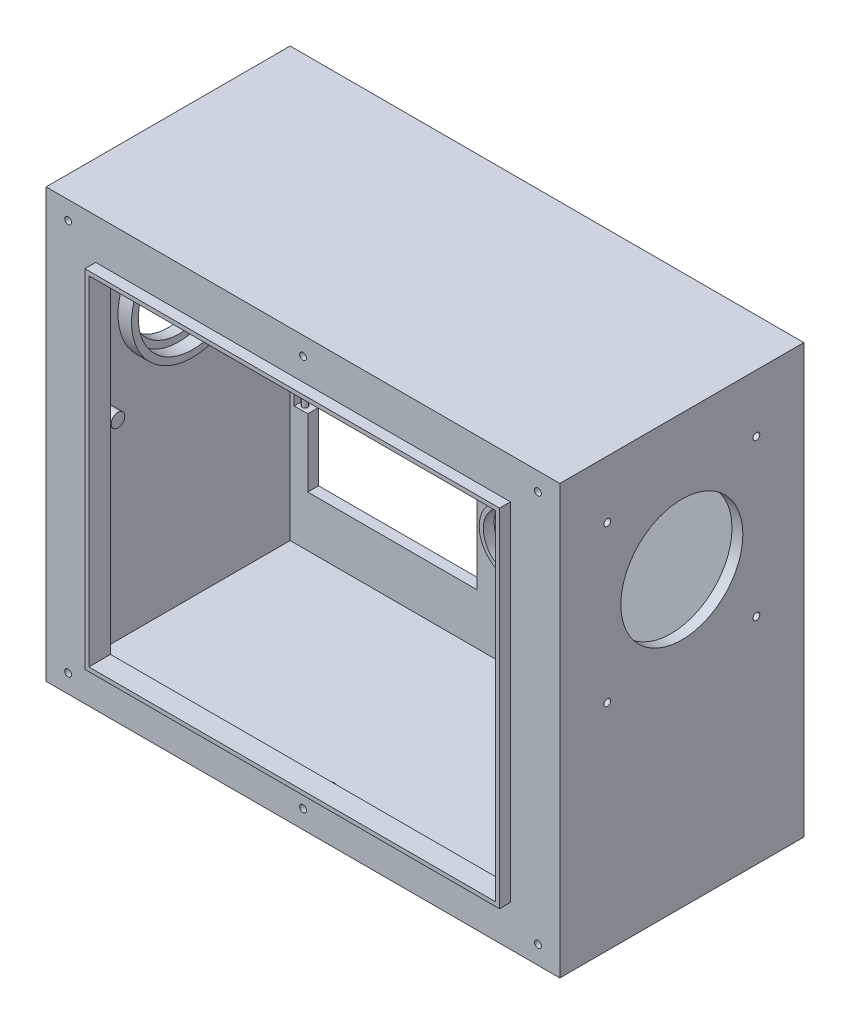
SolidWorks part; units mm, degrees
ref_plane "Alzado" through (0, 0, 0) normal (0, 0, 1) x (1, 0, 0)
ref_plane "Planta" through (0, 0, 0) normal (0, 1, 0) x (1, 0, 0)
ref_plane "Vista lateral" through (0, 0, 0) normal (1, 0, 0) x (0, 0, -1)
sketch "Croquis1" plane through (0, 0, 0) normal (0, 0, 1) x (1, 0, 0)
  line L0 (-189.5, 158) -> (189.5, 158)
  line L1 (-181.5, -150) -> (181.5, -150) construction
  line L2 (-181.5, -150) -> (-181.5, 150) construction
  line L3 (-181.5, 150) -> (181.5, 150) construction
  line L4 (181.5, -150) -> (181.5, 150) construction
  line L5 (-181.5, -150) -> (181.5, 150) construction
  line L6 (-181.5, 150) -> (181.5, -150) construction
  line L7 (189.5, -158) -> (189.5, 158)
  line L8 (-189.5, -158) -> (189.5, -158)
  line L9 (-189.5, -158) -> (-189.5, 158)
  point P0 (0, 0)
  dimension "D1" = 363
  dimension "D2" = 300
  dimension "D3" = 8
extrude "Saliente-Extruir1" add sketch "Croquis1" along normal blind 180
shell "Vaciado1" thickness 8
sketch "Croquis2" plane through (-189.5, 0, 0) normal (-1, 0, 0) x (0, 0, 1)
  line L0 (0, 158) -> (90, 158) construction
  line L1 (180, 158) -> (0, 158) construction
  circle A0 centre (90, 58) radius 35
extrude "Cortar-Extruir4" cut sketch "Croquis2" against normal blind 20 contours A0
sketch "Croquis4" plane through (-181.5, 0, 0) normal (1, 0, 0) x (0, 0, -1)
  circle A1 centre (-90, 58) radius 40
  circle A2 centre (-90, 58) radius 45
extrude "Saliente-Extruir4" add sketch "Croquis4" along normal blind 10
sketch "Croquis6" plane through (189.5, 0, 0) normal (1, 0, 0) x (0, 0, -1)
  line L0 (-90, 158) -> (-90, 58) construction
  line L1 (-180, 158) -> (0, 158) construction
  circle A0 centre (-90, 58) radius 45
  dimension "D1" = 90
extrude "Cortar-Extruir6" cut sketch "Croquis6" against normal blind 10 contours A0
sketch "Croquis7" plane through (0, 0, 8) normal (0, 0, 1) x (1, 0, 0)
  circle A3 centre (0, -53) radius 21
  circle A4 centre (0, -53) radius 24
  dimension "D1" = 42
  dimension "D2" = 48
extrude "Saliente-Extruir9" add sketch "Croquis7" along normal blind 18
ref_plane "Plano6" through (0, 0, 180) normal (0, 0, 1) x (1, 0, 0)
sketch "Croquis11" plane through (0, 0, 180) normal (0, 0, 1) x (1, 0, 0)
  line L1 (181.5, 150) -> (-181.5, 150)
  line L2 (181.5, 150) -> (181.5, -150)
  line L3 (181.5, -150) -> (-181.5, -150)
  line L4 (-181.5, 150) -> (-181.5, -150)
  line L5 (181.5, 150) -> (-181.5, -150) construction
  line L6 (181.5, -150) -> (-181.5, 150) construction
  line L7 (-150, 125) -> (150, 125)
  line L8 (-150, 125) -> (-150, -125)
  line L9 (-150, -125) -> (150, -125)
  line L10 (150, 125) -> (150, -125)
  line L11 (-150, 125) -> (150, -125) construction
  line L12 (-150, -125) -> (150, 125) construction
  point P0 (0, 0)
  point P7 (0, 0)
  dimension "D1" = 300
  dimension "D2" = 250
extrude "Saliente-Extruir10" add sketch "Croquis11" against normal blind 8
sketch "Croquis12" plane through (0, 0, 180) normal (0, 0, 1) x (1, 0, 0)
  line L1 (150, -125) -> (-150, -125)
  line L2 (150, -125) -> (150, 125)
  line L3 (150, 125) -> (-150, 125)
  line L4 (-150, -125) -> (-150, 125)
  line L5 (150, -125) -> (-150, 125) construction
  line L6 (150, 125) -> (-150, -125) construction
  line L7 (153, -128) -> (-153, -128)
  line L8 (153, -128) -> (153, 128)
  line L9 (153, 128) -> (-153, 128)
  line L10 (-153, -128) -> (-153, 128)
  line L11 (153, -128) -> (-153, 128) construction
  line L12 (153, 128) -> (-153, -128) construction
  point P0 (0, 0)
  point P8 (0, 0)
  dimension "D1" = 3
  dimension "D2" = 3
extrude "Saliente-Extruir11" add sketch "Croquis12" along normal blind 8
sketch "Croquis20" plane through (0, 0, 8) normal (0, 0, 1) x (1, 0, 0)
  circle A0 centre (0, -53) radius 18.5
  circle A1 centre (0, -53) radius 21
  circle A2 centre (0, -53) radius 21 construction
  dimension "D1" = 37
extrude "Saliente-Extruir19" add sketch "Croquis20" along normal blind 10
sketch "Croquis32" plane through (-181.5, 0, 0) normal (1, 0, 0) x (0, 0, -1)
  line L0 (-180, 158) -> (0, 158) construction
  line L1 (0, 158) -> (0, -158) construction
  line L2 (-35, 115.5) -> (-145, 115.5) construction
  line L3 (-35, 115.5) -> (-35, 0.5) construction
  line L4 (-35, 0.5) -> (-145, 0.5) construction
  line L5 (-145, 0.5) -> (-145, 115.5) construction
  circle A0 centre (-35, 115.5) radius 5
  circle A1 centre (-145, 115.5) radius 5
  circle A2 centre (-145, 0.5) radius 5
  circle A3 centre (-35, 0.5) radius 5
  dimension "D1" = 10
  dimension "D2" = 42.5
  dimension "D3" = 35
  dimension "D4" = 110
  dimension "D5" = 157.5
extrude "Saliente-Extruir22" add sketch "Croquis32" along normal blind 10
hole_wizard "Taladro roscado M63" positions "Croquis3D6" profile "Croquis26" tap size "M6" standard "DIN"
sketch3d "Croquis3D6"
  line L2 (-189.5, 0.5, 145) -> (-189.5, 115.5, 145) construction
  line L3 (-189.5, 0.5, 145) -> (-189.5, 0.5, 35) construction
  line L4 (-189.5, 0.5, 35) -> (-189.5, 115.5, 35) construction
  line L5 (-189.5, 115.5, 145) -> (-189.5, 115.5, 35) construction
  line L6 (-189.5, 0.5, 145) -> (-189.5, 115.5, 35) construction
  line L7 (-189.5, 0.5, 35) -> (-189.5, 115.5, 145) construction
  circle A1 centre (-189.5, 58, 90) radius 35 construction
  point P0 (-189.5, 115.5, 35)
  point P2 (-189.5, 115.5, 145)
  point P4 (-189.5, 0.5, 145)
  point P6 (-189.5, 0.5, 35)
  point P265 (-189.5, 58, 90)
  point P268 (-224.5, 58, 90)
  dimension "D1" = 115
  dimension "D2" = 0
  dimension "D3" = 110
cosmetic thread "Rosca de taladro1" parameters "D1"=12, "D2"=6
cosmetic thread "Rosca de taladro2" parameters "D1"=12, "D2"=6
cosmetic thread "Rosca de taladro3" parameters "D1"=12, "D2"=6
cosmetic thread "Rosca de taladro4" parameters "D1"=12, "D2"=6
sketch "Croquis26" plane through (-189.5, 115.5, 35) normal (0, 1, 0) x (0, 0, 1)
  line L0 (0, 0) -> (0, 15.5022)
  line L1 (0, 15.5022) -> (2.5, 14)
  line L2 (2.5, 14) -> (2.5, 0)
  line L5 (2.5, 0) -> (0, 0)
  line L10 (0, 15.5022) -> (-2.5, 14) construction
  line L11 (0, -6.35) -> (0, 107.95) construction
  dimension "Diámetro de perforador para roscar" = 5
  dimension "Profundidad de perforador para roscar" = 14
  dimension "Ángulo de perforador" = 118
sketch "Croquis27" plane through (0, 0, 0) normal (0, 0, -1) x (-1, 0, 0)
  circle A0 centre (0, -53) radius 11
  circle A1 centre (0, -53) radius 21 construction
  dimension "D1" = 22
sketch "Croquis28" plane through (0, 0, 0) normal (0, 0, -1) x (-1, 0, 0)
  line L0 (0, 0) -> (106, 0) construction
  line L5 (168.5, 112.5) -> (43.5, 112.5)
  line L6 (168.5, 112.5) -> (168.5, -112.5)
  line L11 (168.5, -112.5) -> (43.5, -112.5)
  line L12 (43.5, 112.5) -> (43.5, -112.5)
  line L13 (168.5, 112.5) -> (43.5, -112.5) construction
  line L14 (168.5, -112.5) -> (43.5, 112.5) construction
  point P0 (106, 0)
  dimension "D1" = 125
  dimension "D2" = 225
  dimension "D3" = 106
extrude "Cortar-Extruir7" cut sketch "Croquis28" against normal blind 8 contours L6 L5 L12 L11
sketch "Croquis29" plane through (0, 0, 0) normal (0, 0, -1) x (-1, 0, 0)
  line L1 (168.5, 112.5) -> (168.5, -112.5) construction
  line L2 (168.5, 62.5) -> (178.5, 62.5)
  line L3 (168.5, 62.5) -> (168.5, 42.5)
  line L4 (168.5, 42.5) -> (178.5, 42.5)
  line L5 (178.5, 62.5) -> (178.5, 42.5)
  line L6 (168.5, 62.5) -> (178.5, 42.5) construction
  line L7 (168.5, 42.5) -> (178.5, 62.5) construction
  line L8 (168.5, -42.5) -> (178.5, -42.5)
  line L9 (168.5, -42.5) -> (168.5, -62.5)
  line L10 (168.5, -62.5) -> (178.5, -62.5)
  line L11 (178.5, -42.5) -> (178.5, -62.5)
  line L12 (168.5, -42.5) -> (178.5, -62.5) construction
  line L13 (168.5, -62.5) -> (178.5, -42.5) construction
  point P0 (173.5, -52.5)
  point P2 (173.5, 52.5)
  dimension "D1" = 50
  dimension "D2" = 20
  dimension "D3" = 10
  dimension "D4" = 50
  dimension "D5" = 20
  dimension "D6" = 10
extrude "Cortar-Extruir9" cut sketch "Croquis29" against normal blind 8
sketch "Croquis30" plane through (0, 42.5, 0) normal (0, 1, 0) x (1, 0, 0)
  line L4 (-178.5, -8) -> (-178.5, 0) construction
  line L5 (-168.5, 0) -> (-178.5, 0) construction
  circle A1 centre (-174.5, -4) radius 2
  dimension "D1" = 4
  dimension "D2" = 4
  dimension "D3" = 4
extrude "Saliente-Extruir20" add sketch "Croquis30" along normal blind 9
sketch "Croquis31" plane through (0, -62.5, 0) normal (0, 1, 0) x (1, 0, 0)
  line L0 (-178.5, -8) -> (-178.5, 0) construction
  line L1 (-168.5, 0) -> (-178.5, 0) construction
  circle A0 centre (-174.5, -4) radius 2
  dimension "D3" = 4
  dimension "D1" = 4
  dimension "D2" = 4
extrude "Saliente-Extruir21" add sketch "Croquis31" along normal blind 9
mirror "Simetría1" about plane through (0, 0, 0) normal (1, 0, 0) of "Saliente-Extruir22"
sketch "Croquis33" plane through (0, 0, 180) normal (0, 0, 1) x (1, 0, 0)
  line L0 (-568.5, 474) -> (189.5, -158) construction
  line L2 (189.5, 158) -> (-189.5, -158) construction
  line L3 (0, 158) -> (0, -158) construction
  line L4 (189.5, 158) -> (-189.5, 158) construction
  line L5 (-189.5, -158) -> (189.5, -158) construction
  circle A0 centre (0, 144.5) radius 5
  circle A1 centre (0, -144.5) radius 5
  circle A2 centre (173.3085, -144.5) radius 5
  circle A3 centre (173.3085, 144.5) radius 5
  circle A4 centre (-173.3085, 144.5) radius 5
  circle A5 centre (-173.3085, -144.5) radius 5
  point P4 (-189.5, 158)
  point P28 (-568.5, 474)
  dimension "D2" = 10
  dimension "D1" = 13.5
  dimension "D3" = 13.5
  dimension "D4" = 13.5
  dimension "D5" = 13.5
  dimension "D6" = 13.5
  dimension "D7" = 13.5
extrude "Saliente-Extruir23" add sketch "Croquis33" against normal blind 15 from surface at -8 starting at face at (0, 0, 172)
hole_wizard "Taladro roscado M64" positions "Croquis3D7" profile "Croquis35" tap size "M6" standard "DIN"
sketch3d "Croquis3D7"
  line L0 (-189.5, 158, 180) -> (189.5, -158, 180) construction
  line L2 (189.5, 158, 180) -> (-189.5, -158, 180) construction
  line L4 (0, 158, 180) -> (0, -158, 180) construction
  line L5 (189.5, 158, 180) -> (-189.5, 158, 180) construction
  line L6 (-189.5, -158, 180) -> (189.5, -158, 180) construction
  point P0 (-173.3085, 144.5, 180)
  point P2 (0, 144.5, 180)
  point P4 (173.3085, 144.5, 180)
  point P6 (173.3085, -144.5, 180)
  point P8 (0, -144.5, 180)
  point P10 (-173.3085, -144.5, 180)
  point P30 (0, 0, 0)
  point P31 (0, 0, 0)
  point P32 (0, 0, 0)
  point P33 (0, 0, 0)
  point P34 (0, 0, 0)
  point P35 (0, 0, 0)
  dimension "D1" = 13.5
  dimension "D2" = 13.5
  dimension "D3" = 13.5
  dimension "D4" = 13.5
  dimension "D5" = 13.5
  dimension "D6" = 13.5
sketch "Croquis35" plane through (-173.3085, 144.5, 180) normal (1, 0, 0) x (0, -1, 0)
  line L0 (0, 0) -> (0, 18.5022)
  line L1 (0, 18.5022) -> (2.5, 17)
  line L2 (2.5, 17) -> (2.5, 0)
  line L5 (2.5, 0) -> (0, 0)
  line L10 (0, 18.5022) -> (-2.5, 17) construction
  line L11 (0, -6.35) -> (0, 107.95) construction
  dimension "Diámetro de perforador para roscar" = 5
  dimension "Profundidad de perforador para roscar" = 17
  dimension "Ángulo de perforador" = 118
cosmetic thread "Rosca de taladro5" parameters "D1"=12, "D2"=6
cosmetic thread "Rosca de taladro6" parameters "D1"=12, "D2"=6
cosmetic thread "Rosca de taladro7" parameters "D1"=12, "D2"=6
cosmetic thread "Rosca de taladro8" parameters "D1"=12, "D2"=6
cosmetic thread "Rosca de taladro9" parameters "D1"=12, "D2"=6
cosmetic thread "Rosca de taladro10" parameters "D1"=12, "D2"=6
mirror "Simetría2" about plane through (0, 0, 0) normal (1, 0, 0) of "Taladro roscado M63"
cosmetic thread "Rosca de taladro11" parameters "D1"=12, "D2"=6
cosmetic thread "Rosca de taladro12" parameters "D1"=12, "D2"=6
cosmetic thread "Rosca de taladro13" parameters "D1"=12, "D2"=6
cosmetic thread "Rosca de taladro14" parameters "D1"=12, "D2"=6
